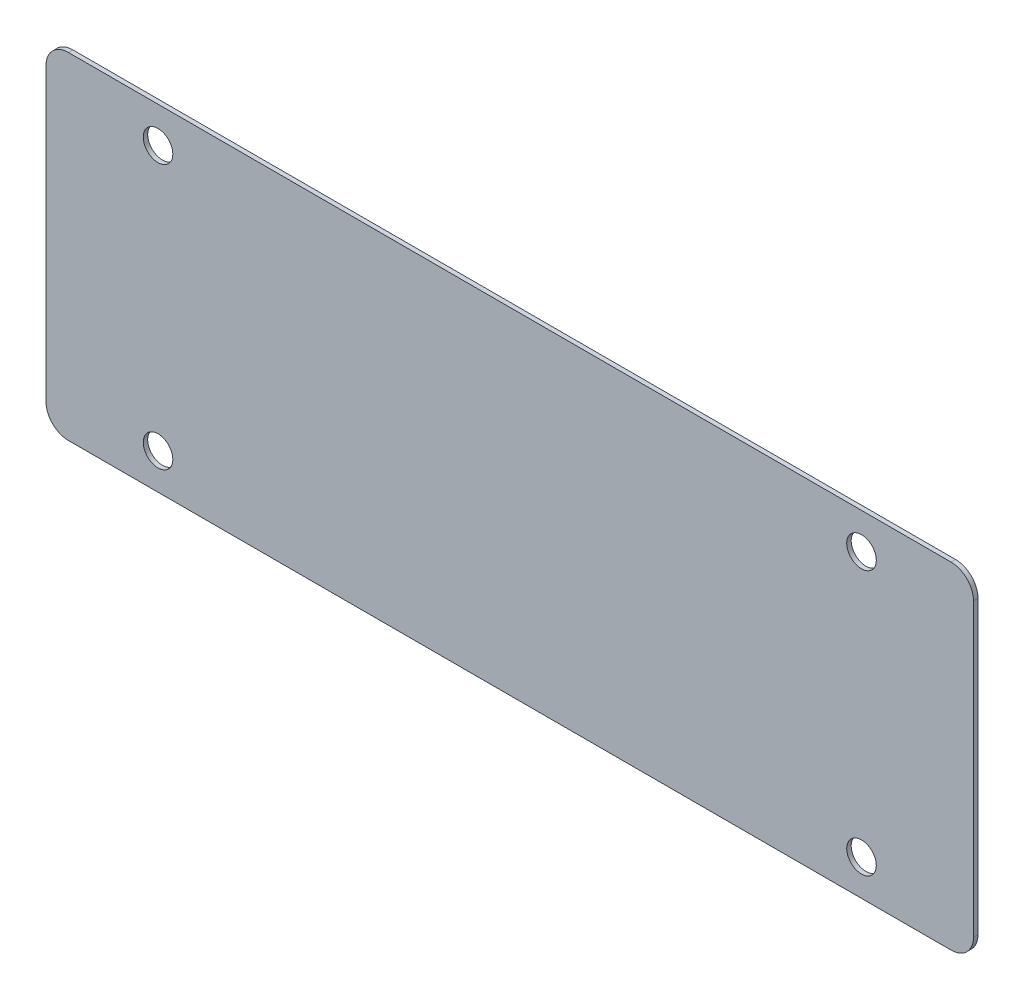
SolidWorks part; units mm, degrees
ref_plane "前视基准面" through (0, 0, 0) normal (0, 0, 1) x (1, 0, 0)
ref_plane "上视基准面" through (0, 0, 0) normal (0, 1, 0) x (1, 0, 0)
ref_plane "右视基准面" through (0, 0, 0) normal (1, 0, 0) x (0, 0, -1)
sketch "草图1" plane through (0, 0, 0) normal (0, 0, 1) x (1, 0, 0)
  line L1 (-103.5, 37.5) -> (103.5, 37.5)
  line L2 (-103.5, 37.5) -> (-103.5, -37.5)
  line L3 (-103.5, -37.5) -> (103.5, -37.5)
  line L4 (103.5, 37.5) -> (103.5, -37.5)
  line L5 (-103.5, 37.5) -> (103.5, -37.5) construction
  line L6 (-103.5, -37.5) -> (103.5, 37.5) construction
  point P0 (0, 0)
  dimension "D1" = 207
  dimension "D2" = 75
extrude "凸台-拉伸1" add sketch "草图1" along normal blind 1
sketch "草图2" plane through (0, 0, 1) normal (0, 0, 1) x (1, 0, 0)
  line L0 (103.5, 37.5) -> (-103.5, 37.5) construction
  line L1 (-78.5, -29.5) -> (78.5, -29.5) construction
  line L2 (-78.5, -29.5) -> (-78.5, 29.5) construction
  line L3 (-78.5, 29.5) -> (78.5, 29.5) construction
  line L4 (78.5, -29.5) -> (78.5, 29.5) construction
  line L5 (-78.5, -29.5) -> (78.5, 29.5) construction
  line L6 (-78.5, 29.5) -> (78.5, -29.5) construction
  line L7 (-103.5, 37.5) -> (-103.5, -37.5) construction
  circle A0 centre (-78.5, 29.5) radius 3.3
  circle A1 centre (78.5, 29.5) radius 3.3
  circle A2 centre (-78.5, -29.5) radius 3.3
  circle A3 centre (78.5, -29.5) radius 3.3
  point P0 (0, 0)
  dimension "D3" = 6.6
  dimension "D1" = 25
  dimension "D2" = 8
extrude "切除-拉伸1" cut sketch "草图2" against normal through all
fillet "圆角1" radius 5 4 edges at (-103.5, -37.5, 0.5) (103.5, -37.5, 0.5) (-103.5, 37.5, 0.5) (103.5, 37.5, 0.5)
